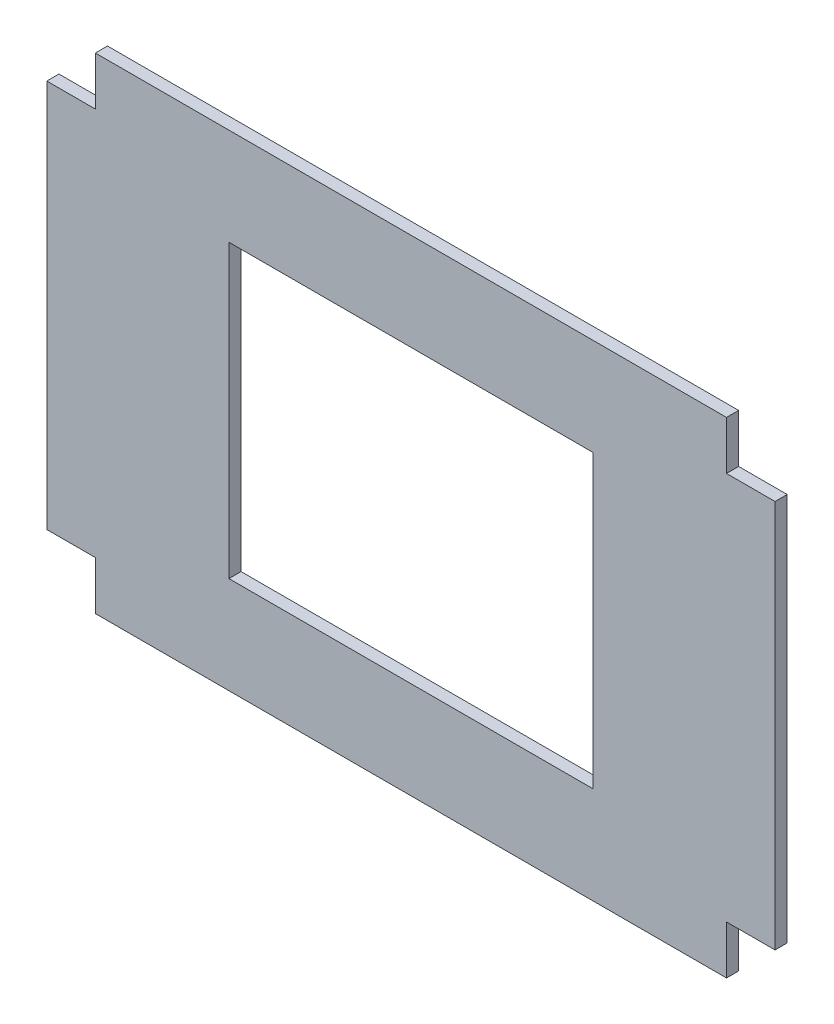
SolidWorks part; units mm, degrees
ref_plane "Alzado" through (0, 0, 0) normal (0, 0, 1) x (1, 0, 0)
ref_plane "Planta" through (0, 0, 0) normal (0, 1, 0) x (1, 0, 0)
ref_plane "Vista lateral" through (0, 0, 0) normal (1, 0, 0) x (0, 0, -1)
sketch "Croquis1" plane through (0, 0, 0) normal (0, 0, 1) x (1, 0, 0)
  line L1 (-294.9346, 8.7369) -> (5.0654, 8.7369)
  line L2 (-294.9346, 8.7369) -> (-294.9346, -191.2631)
  line L3 (-294.9346, -191.2631) -> (5.0654, -191.2631)
  line L4 (5.0654, 8.7369) -> (5.0654, -191.2631)
  line L5 (-294.9346, 8.7369) -> (5.0654, -191.2631) construction
  line L6 (-294.9346, -191.2631) -> (5.0654, 8.7369) construction
  point P0 (-144.9346, -91.2631)
  dimension "D1" = 300
  dimension "D2" = 200
extrude "Saliente-Extruir1" add sketch "Croquis1" along normal blind 5
sketch "Croquis4" plane through (0, 0, 5) normal (0, 0, 1) x (1, 0, 0)
  line L0 (-294.9346, -91.2631) -> (5.0654, -91.2631) construction
  line L1 (-294.9346, 8.7369) -> (-274.9346, 8.7369)
  line L2 (-294.9346, 8.7369) -> (-294.9346, -11.2631)
  line L3 (-294.9346, -11.2631) -> (-274.9346, -11.2631)
  line L4 (-274.9346, 8.7369) -> (-274.9346, -11.2631)
  line L5 (-294.9346, 8.7369) -> (-294.9346, -191.2631) construction
  line L6 (5.0654, -191.2631) -> (5.0654, 8.7369) construction
  line L7 (-144.9346, -91.2631) -> (-144.9346, 8.7369) construction
  line L8 (5.0654, 8.7369) -> (5.0654, -11.2631)
  line L9 (5.0654, 8.7369) -> (-14.9346, 8.7369)
  line L10 (-14.9346, 8.7369) -> (-14.9346, -11.2631)
  line L11 (5.0654, -11.2631) -> (-14.9346, -11.2631)
  line L12 (-274.9346, -191.2631) -> (-274.9346, -171.2631)
  line L13 (-294.9346, -171.2631) -> (-274.9346, -171.2631)
  line L14 (-294.9346, -191.2631) -> (-294.9346, -171.2631)
  line L15 (-294.9346, -191.2631) -> (-274.9346, -191.2631)
  line L16 (5.0654, -171.2631) -> (-14.9346, -171.2631)
  line L17 (5.0654, -191.2631) -> (5.0654, -171.2631)
  line L18 (5.0654, -191.2631) -> (-14.9346, -191.2631)
  line L19 (-14.9346, -191.2631) -> (-14.9346, -171.2631)
  dimension "D1" = 20
extrude "Cortar-Extruir4" cut sketch "Croquis4" against normal blind 10
sketch "Croquis5" plane through (0, 0, 5) normal (0, 0, 1) x (1, 0, 0)
  line L9 (-294.9346, -91.2631) -> (5.0654, -91.2631) construction
  line L14 (-294.9346, -11.2631) -> (-294.9346, -171.2631) construction
  line L15 (5.0654, -171.2631) -> (5.0654, -11.2631) construction
  line L17 (-69.9346, -151.2631) -> (-219.9346, -151.2631)
  line L18 (-69.9346, -151.2631) -> (-69.9346, -31.2631)
  line L19 (-69.9346, -31.2631) -> (-219.9346, -31.2631)
  line L20 (-219.9346, -151.2631) -> (-219.9346, -31.2631)
  line L21 (-69.9346, -151.2631) -> (-219.9346, -31.2631) construction
  line L22 (-69.9346, -31.2631) -> (-219.9346, -151.2631) construction
  point P15 (-144.9346, -91.2631)
  point P20 (0, 0)
  dimension "D1" = 150
  dimension "D2" = 120
extrude "Cortar-Extruir6" cut sketch "Croquis5" against normal blind 10
